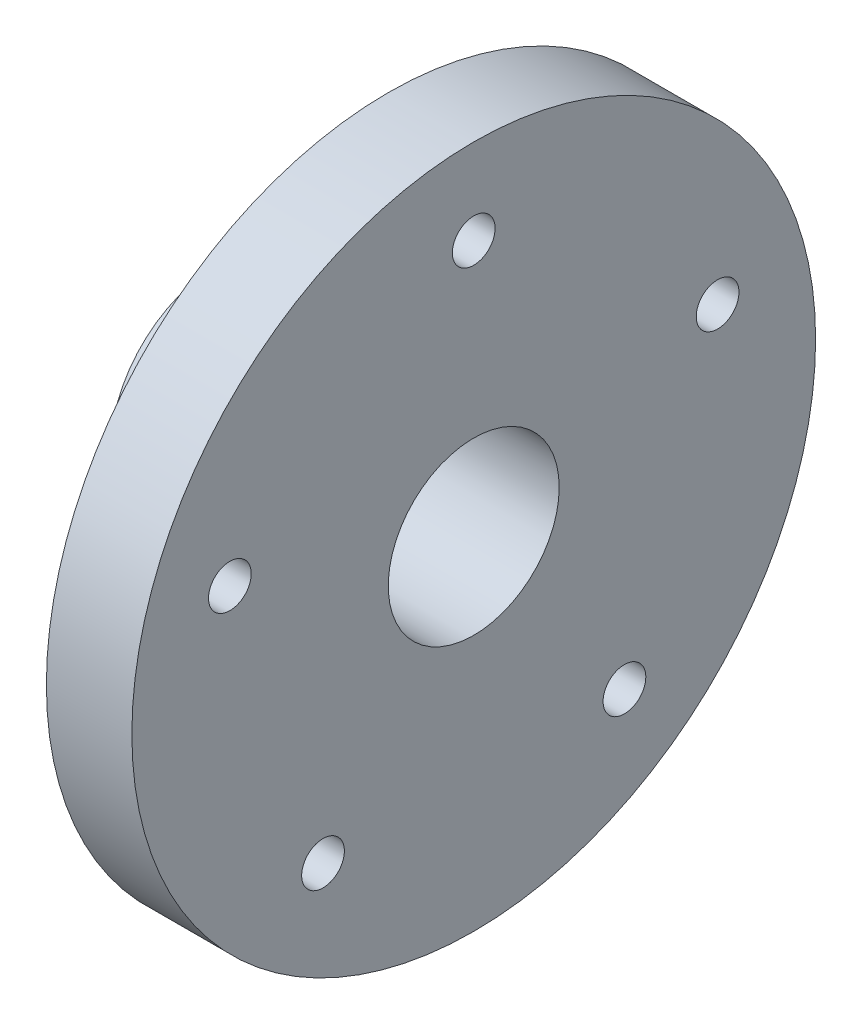
SolidWorks part; units mm, degrees
ref_plane "Front Plane" through (0, 0, 0) normal (0, 0, 1) x (1, 0, 0)
ref_plane "Top Plane" through (0, 0, 0) normal (0, 1, 0) x (1, 0, 0)
ref_plane "Right Plane" through (0, 0, 0) normal (1, 0, 0) x (0, 0, -1)
sketch "Sketch2" plane through (0, 0, 0) normal (1, 0, 0) x (0, 0, -1)
  circle A0 centre (0, 0) radius 4
  dimension "D1" = 8
extrude "Boss-Extrude1" add sketch "Sketch2" against normal blind 1
sketch "Sketch3" plane through (-1, 0, 0) normal (-1, 0, 0) x (0, 0, 1)
  circle A0 centre (0, 0) radius 1
  dimension "D1" = 2
sketch "Sketch4" plane through (0, 0, 0) normal (1, 0, 0) x (0, 0, -1)
  circle A0 centre (0, 0) radius 1
  dimension "D1" = 2
sketch "Sketch5" plane through (0, 0, 0) normal (1, 0, 0) x (0, 0, -1)
  line L0 (0, 0) -> (0, 4.8235) construction
  circle A0 centre (0, 3) radius 0.25
  dimension "D2" = 0.5
  dimension "D1" = 3
extrude "Cut-Extrude1" cut sketch "Sketch4" against normal blind 2.5
sketch "Sketch6" plane through (-1, 0, 0) normal (-1, 0, 0) x (0, 0, 1)
  circle A0 centre (0, 0) radius 1.25
  circle A1 centre (0, 0) radius 1 construction
  circle A2 centre (0, 0) radius 1
  dimension "D1" = 2.5
extrude "Boss-Extrude4" add sketch "Sketch6" along normal blind 2
extrude "Cut-Extrude2" cut sketch "Sketch5" against normal blind 2
pattern_circular "CirPattern1" count 5 over 360 about axis through (0, 0, 0) along (1, 0, 0) of "Cut-Extrude2"
